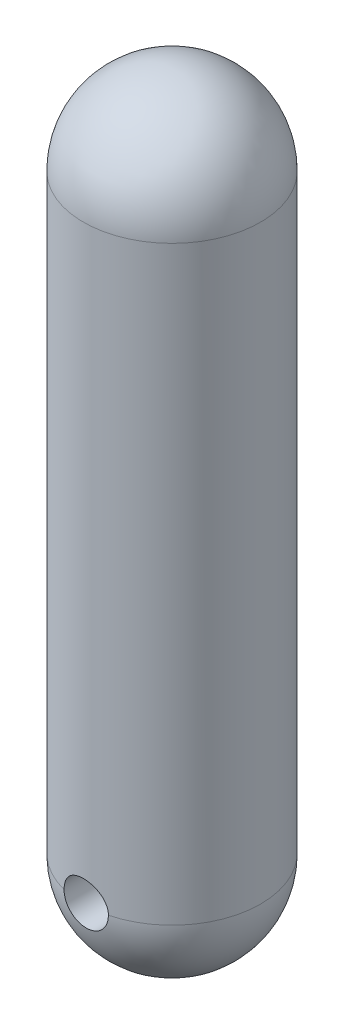
SolidWorks part; units mm, degrees
ref_plane "Front Plane" through (0, 0, 0) normal (0, 0, 1) x (1, 0, 0)
ref_plane "Top Plane" through (0, 0, 0) normal (0, 1, 0) x (1, 0, 0)
ref_plane "Right Plane" through (0, 0, 0) normal (1, 0, 0) x (0, 0, -1)
sketch "Sketch1" plane through (0, 0, 0) normal (0, 0, 1) x (1, 0, 0)
  line L0 (0, 0) -> (0, 100)
  line L1 (0, 100) -> (-15, 100)
  line L2 (-15, 100) -> (-15, 0)
  line L3 (-15, 0) -> (0, 0)
  line L4 (0, 0) -> (0, -15)
  line L5 (0, 100) -> (0, 115)
  arc A0 (0, 115) -> (-15, 100) centre (0, 100) ccw
  arc A1 (-15, 0) -> (0, -15) centre (0, 0) ccw
  dimension "D1" = 100
  dimension "D2" = 15
revolve "Revolve1" add sketch "Sketch1" angle 360 about L0
sketch "Sketch2" plane through (0, 0, 0) normal (0, 0, 1) x (1, 0, 0)
  circle A0 centre (0, 0) radius 3.75
  dimension "D1" = 7.5
extrude "Cut-Extrude1" cut sketch "Sketch2" against normal through all both and the other way through all
